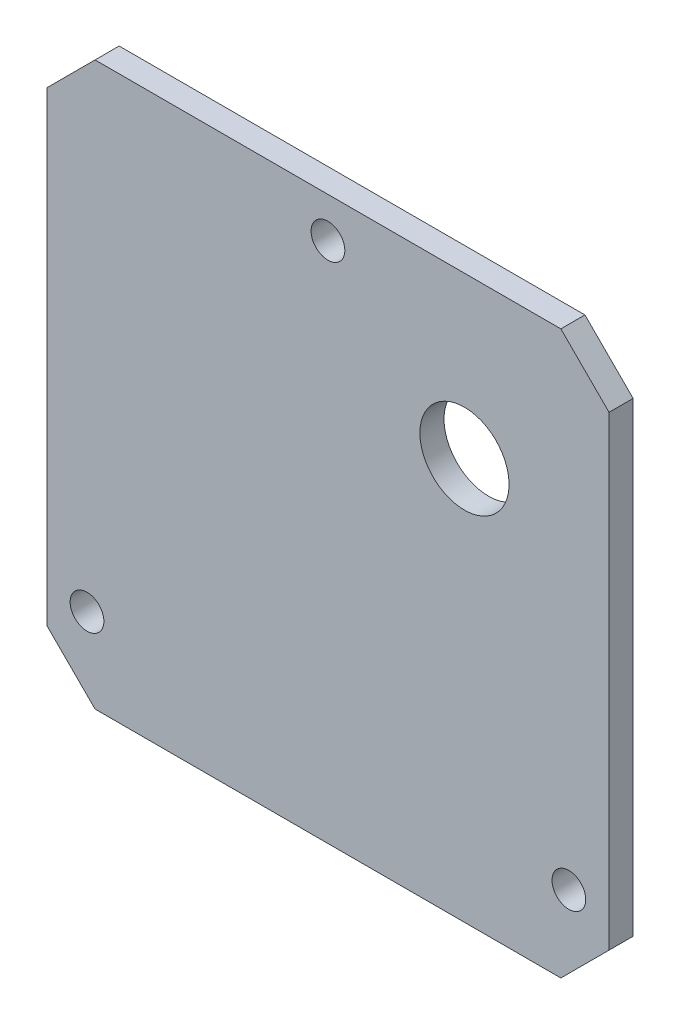
SolidWorks part; units mm, degrees
material "5052-O"
ref_plane "前基準面" through (0, 0, 0) normal (0, 0, 1) x (1, 0, 0)
ref_plane "上基準面" through (0, 0, 0) normal (0, 1, 0) x (1, 0, 0)
ref_plane "右基準面" through (0, 0, 0) normal (1, 0, 0) x (0, 0, -1)
sketch "草圖1" plane through (0, 0, 0) normal (0, 0, 1) x (1, 0, 0)
  line L1 (35, -35) -> (-35, -35)
  line L2 (35, -35) -> (35, 35)
  line L3 (35, 35) -> (-35, 35)
  line L4 (-35, -35) -> (-35, 35)
  line L5 (35, -35) -> (-35, 35) construction
  line L6 (35, 35) -> (-35, -35) construction
  point P0 (0, 0)
  dimension "D1" = 70
  dimension "D2" = 70
extrude "填料-伸長1" add sketch "草圖1" along normal blind 3
chamfer "導角1" distance 6 angle 45 4 edges at (-35, -35, 1.5) (35, -35, 1.5) (35, 35, 1.5) (-35, 35, 1.5)
sketch "草圖2" plane through (0, 0, 0) normal (0, 0, -1) x (-1, 0, 0)
  line L0 (-29, 35) -> (29, 35) construction
  line L1 (35, 29) -> (35, -29) construction
  circle A0 centre (0, 30) radius 2.1
  circle A1 centre (-30, -25) radius 2.1
  circle A2 centre (30, -25) radius 2.1
  dimension "D1" = 4.2
  dimension "D2" = 5
  dimension "D3" = 35
  dimension "D4" = 55
  dimension "D5" = 30
  dimension "D6" = 30
  dimension "D7" = 55
extrude "除料-伸長1" cut sketch "草圖2" against normal through all
sketch "草圖3" plane through (0, 0, 0) normal (0, 0, -1) x (-1, 0, 0)
  line L1 (-29, 35) -> (29, 35) construction
  line L2 (-35, -29) -> (-35, 29) construction
  circle A0 centre (-17, 15) radius 5.55
  dimension "D1" = 18
  dimension "D2" = 20
  dimension "D3" = 11.1
extrude "除料-伸長2" cut sketch "草圖3" against normal through all
